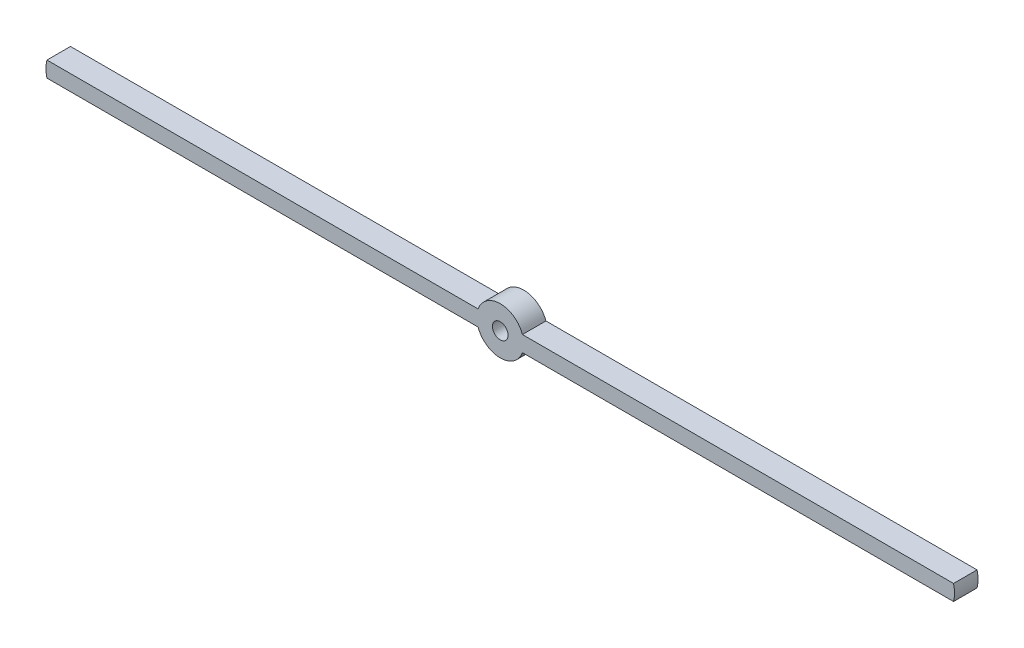
SolidWorks part; units mm, degrees
ref_plane "Plan de face" through (0, 0, 0) normal (0, 0, 1) x (1, 0, 0)
ref_plane "Plan de dessus" through (0, 0, 0) normal (0, 1, 0) x (1, 0, 0)
ref_plane "Plan de droite" through (0, 0, 0) normal (1, 0, 0) x (0, 0, -1)
sketch "Esquisse1" plane through (0, 0, 0) normal (0, 0, 1) x (1, 0, 0)
  line L1 (-5.6569, 2) -> (-115.6569, 2)
  line L2 (-5.6569, 2) -> (-5.6569, -2) construction
  line L3 (-5.6569, -2) -> (-115.6569, -2)
  line L4 (-115.6569, 2) -> (-115.6569, -2) construction
  line L5 (5.6569, 2) -> (115.6569, 2)
  line L6 (5.6569, 2) -> (5.6569, -2) construction
  line L7 (5.6569, -2) -> (115.6569, -2)
  line L8 (115.6569, 2) -> (115.6569, -2) construction
  circle A0 centre (0, 0) radius 2
  circle A1 centre (0, 0) radius 6 construction
  arc A2 (-115.6569, 2) -> (-115.6569, -2) centre (-107.9109, 0) ccw
  arc A3 (115.6569, 2) -> (115.6569, -2) centre (107.9109, 0) cw
  arc A4 (-5.6569, 2) -> (5.6569, 2) centre (0, 0) cw
  arc A5 (5.6569, -2) -> (-5.6569, -2) centre (0, 0) cw
extrude "Boss.-Extru.1" add sketch "Esquisse1" along normal blind 6 contours A0 | L3 A2 L1 A4 L5 A3 L7 A5
